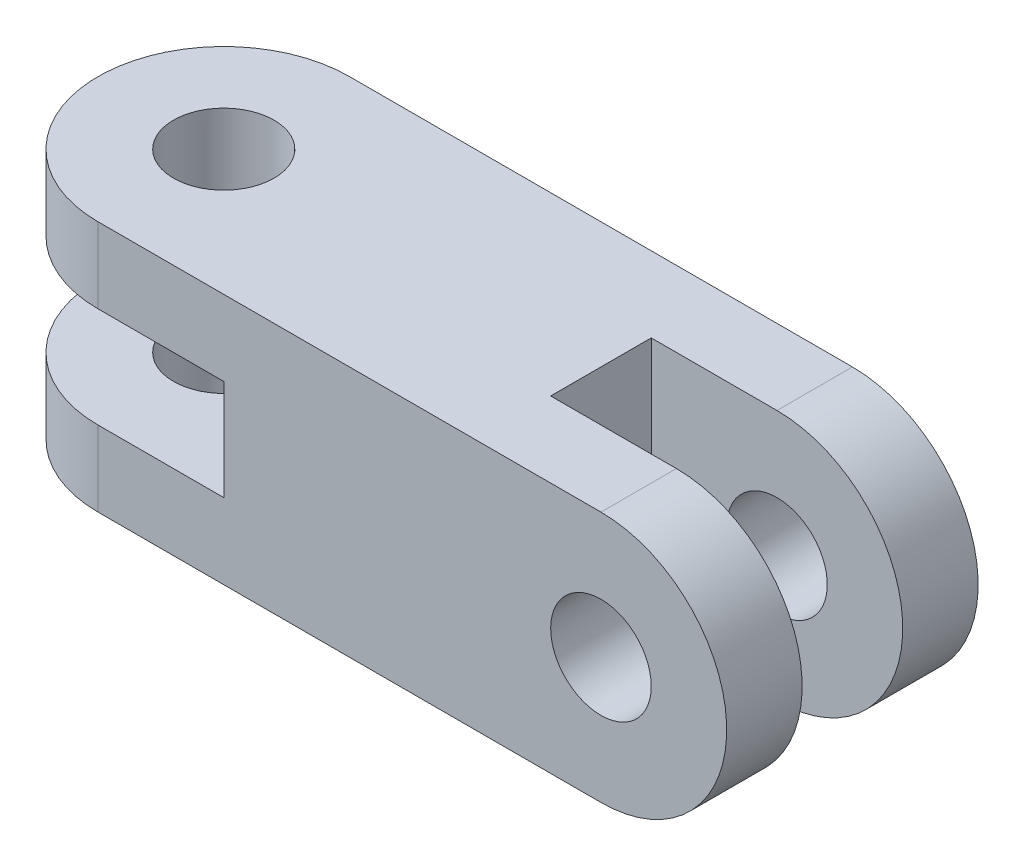
SolidWorks part; units mm, degrees
ref_plane "Front Plane" through (0, 0, 0) normal (0, 0, 1) x (1, 0, 0)
ref_plane "Top Plane" through (0, 0, 0) normal (0, 1, 0) x (1, 0, 0)
ref_plane "Right Plane" through (0, 0, 0) normal (1, 0, 0) x (0, 0, -1)
sketch "Sketch1" plane through (0, 0, 0) normal (0, 0, 1) x (1, 0, 0)
  line L0 (0, 25) -> (-125, 25)
  line L1 (0, 0) -> (-128.7872, 0) construction
  line L2 (-125, 25) -> (-125, 10)
  line L3 (-125, 10) -> (-75, 10)
  line L4 (-75, 10) -> (-75, -10)
  line L5 (-125, -10) -> (-75, -10)
  line L6 (-125, -25) -> (-125, -10)
  line L7 (0, -25) -> (-125, -25)
  arc A0 (0, -25) -> (0, 25) centre (0, 0) ccw
  circle A1 centre (0, 0) radius 10
  point P11 (-75, 0)
  dimension "D1" = 50
  dimension "D2" = 20
  dimension "D3" = 125
  dimension "D4" = 50
  dimension "D5" = 15
extrude "Boss-Extrude1" add sketch "Sketch1" along normal blind 50
sketch "Sketch3" plane through (0, -25, 0) normal (0, -1, 0) x (1, 0, 0)
  line L0 (-125, 50) -> (-125, 0) construction
  line L1 (-125, 50) -> (0, 50) construction
  line L2 (25, 0) -> (25, 50) construction
  line L3 (-25, 15) -> (25, 15)
  line L4 (-25, 15) -> (-25, 35)
  line L5 (-25, 35) -> (25, 35)
  line L6 (-125, 0) -> (0, 0)
  line L7 (0, 0) -> (0, 50)
  line L8 (0, 50) -> (-125, 50)
  line L9 (-125, 50) -> (-125, 0)
  line L10 (-125, 0) -> (-100, 0)
  line L12 (-100, 50) -> (-125, 50)
  line L13 (-125, 50) -> (-125, 0)
  line L14 (25, 15) -> (25, 35)
  line L15 (-25, 15) -> (25, 35) construction
  line L16 (-25, 35) -> (25, 15) construction
  line L17 (25, 50) -> (0, 50) construction
  arc A0 (-100, 50) -> (-100, 0) centre (-100, 25) ccw
  circle A1 centre (-100, 25) radius 10
  point P1 (0, 25)
  line M5 (-125, 0) -> (0, 0)
  line M6 (0, 0) -> (0, 50)
  line M7 (0, 50) -> (-125, 50)
  line M8 (-125, 50) -> (-125, 0)
  dimension "D1" = 50
  dimension "D5" = 20
  dimension "D3" = 15
  dimension "D4" = 50
  dimension "D2" = 0
extrude "Cut-Extrude2" cut sketch "Sketch3" against normal through all contours A0 M7 M8 | A0 L13 M5 | L3 L14 L5 M6 | L5 L4 L3 M6 | A1
